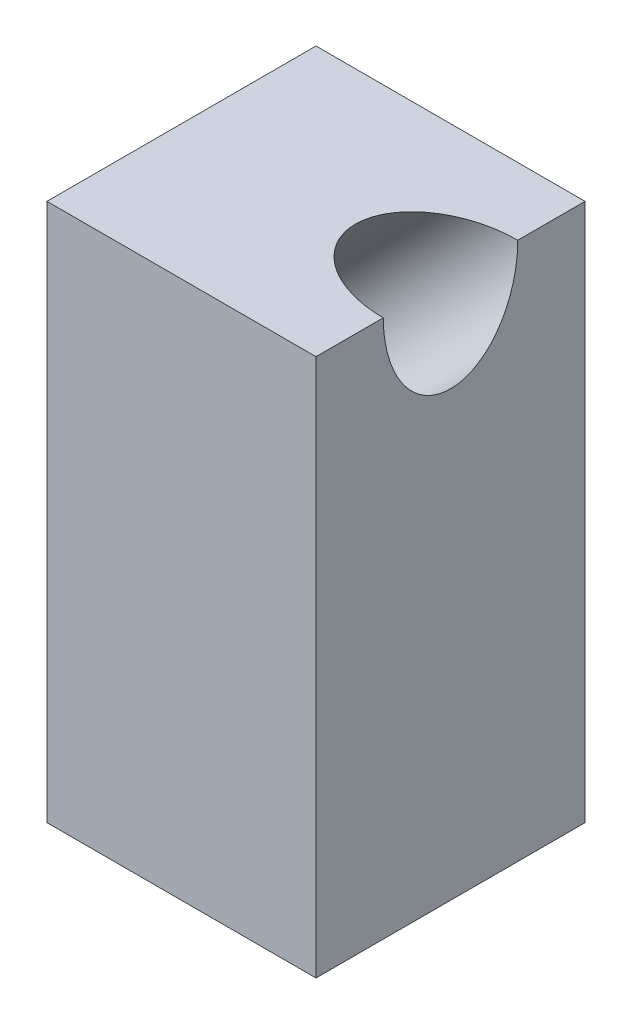
SolidWorks part; units mm, degrees
ref_plane "Front Plane" through (0, 0, 0) normal (0, 0, 1) x (1, 0, 0)
ref_plane "Top Plane" through (0, 0, 0) normal (0, 1, 0) x (1, 0, 0)
ref_plane "Right Plane" through (0, 0, 0) normal (1, 0, 0) x (0, 0, -1)
sketch "Sketch1" plane through (0, 0, 0) normal (0, 0, 1) x (1, 0, 0)
  line L1 (0, 0) -> (25.4, 0)
  line L2 (0, 0) -> (0, 50.8)
  line L3 (0, 50.8) -> (25.4, 50.8)
  line L4 (25.4, 0) -> (25.4, 50.8)
  dimension "D1" = 25.4
  dimension "D2" = 50.8
extrude "Boss-Extrude1" add sketch "Sketch1" along normal blind 25.4 contours L2 L1 L4 L3
ref_plane "Plane1" through (38.1, 38.1, 0) normal (0.7071, 0.7071, 0) x (0.7071, -0.7071, 0)
sketch "Sketch2" plane through (38.1, 38.1, 0) normal (0.7071, 0.7071, 0) x (0.7071, -0.7071, 0)
  line L0 (-17.9605, -25.4) -> (-17.9605, 0) construction
  circle A0 centre (-17.9605, -12.7) radius 6.35
  point P4 (0, 0)
  dimension "D1" = 12.7
extrude "Cut-Extrude1" cut sketch "Sketch2" against normal blind 50.8 contours A0
